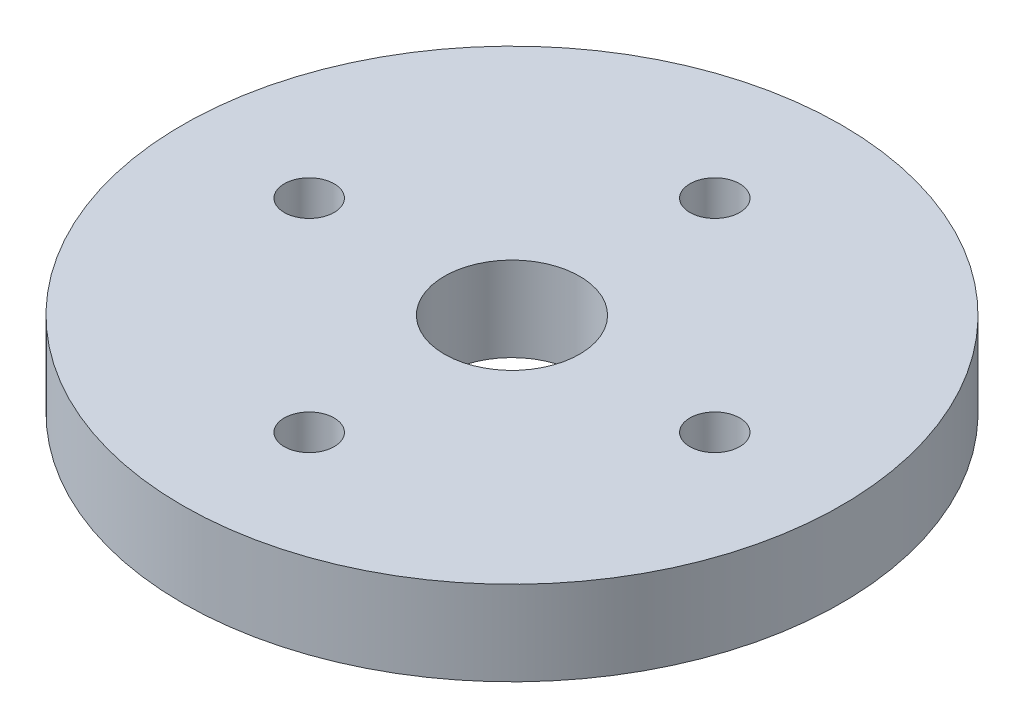
SolidWorks part; units mm, degrees
ref_plane "Front Plane" through (0, 0, 0) normal (0, 0, 1) x (1, 0, 0)
ref_plane "Top Plane" through (0, 0, 0) normal (0, 1, 0) x (1, 0, 0)
ref_plane "Right Plane" through (0, 0, 0) normal (1, 0, 0) x (0, 0, -1)
sketch "Sketch1" plane through (0, 0, 0) normal (0, 1, 0) x (1, 0, 0)
  line L0 (0, 19.5) -> (0, -19.5) construction
  line L1 (-19.5, 0) -> (19.5, 0) construction
  circle A0 centre (0, 0) radius 19.5
  circle A1 centre (0, 0) radius 4
  circle A2 centre (0, 12) radius 1.475
  circle A3 centre (-12, 0) radius 1.475
  circle A4 centre (12, 0) radius 1.475
  circle A5 centre (0, -12) radius 1.475
  dimension "D1" = 39
  dimension "D2" = 8
  dimension "D4" = 2.95
  dimension "D3" = 12
  dimension "D5" = 12
extrude "Boss-Extrude1" add sketch "Sketch1" along normal blind 5
